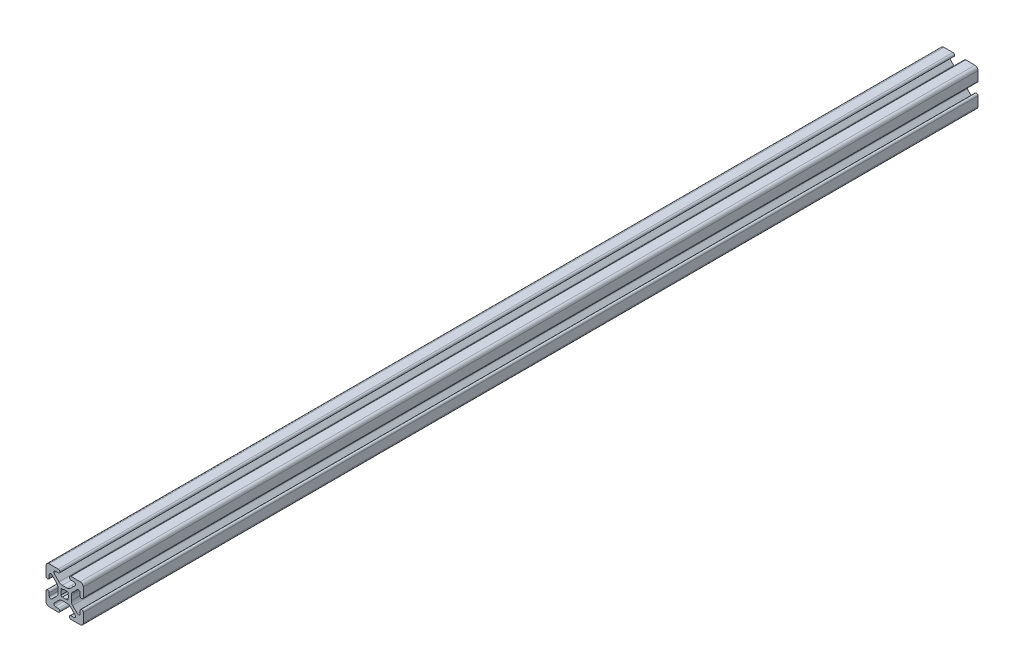
SolidWorks part; units mm, degrees
ref_plane "Front Plane" through (0, 0, 0) normal (0, 0, 1) x (1, 0, 0)
ref_plane "Top Plane" through (0, 0, 0) normal (0, 1, 0) x (1, 0, 0)
ref_plane "Right Plane" through (0, 0, 0) normal (1, 0, 0) x (0, 0, -1)
ref_plane "Plane1" through (0, 0, 304.8) normal (0, 0, 1) x (1, 0, 0)
sketch "Sketch1" plane through (0, 0, 304.8) normal (0, 0, 1) x (1, 0, 0)
  line L0 (-12.7, -4.3561) -> (-12.7, -10.5918)
  line L1 (-10.5918, -12.7) -> (-4.3561, -12.7)
  line L2 (-4.3561, -10.4902) -> (-6.3701, -10.4902)
  line L3 (-7.1192, -8.6817) -> (-3.8846, -5.4471)
  line L4 (-1.6396, -4.5172) -> (1.6396, -4.5172)
  line L5 (3.8846, -5.4471) -> (7.1192, -8.6817)
  line L6 (6.3701, -10.4902) -> (4.3561, -10.4902)
  line L7 (4.3561, -12.7) -> (10.5918, -12.7)
  line L8 (12.7, -10.5918) -> (12.7, -4.3561)
  line L9 (10.4902, -4.3561) -> (10.4902, -6.3701)
  line L10 (8.6817, -7.1192) -> (5.4471, -3.8846)
  line L11 (4.5172, -1.6396) -> (4.5172, 1.6396)
  line L12 (5.4471, 3.8846) -> (8.6817, 7.1192)
  line L13 (10.4902, 6.3701) -> (10.4902, 4.3561)
  line L14 (12.7, 4.3561) -> (12.7, 10.5918)
  line L15 (10.5918, 12.7) -> (4.3561, 12.7)
  line L16 (4.3561, 10.4902) -> (6.3701, 10.4902)
  line L17 (7.1192, 8.6817) -> (3.8846, 5.4471)
  line L18 (1.6396, 4.5172) -> (-1.6396, 4.5172)
  line L19 (-3.8846, 5.4471) -> (-7.1192, 8.6817)
  line L20 (-6.3701, 10.4902) -> (-4.3561, 10.4902)
  line L21 (-4.3561, 12.7) -> (-10.5918, 12.7)
  line L22 (-12.7, 10.5918) -> (-12.7, 4.3561)
  line L23 (-10.4902, 4.3561) -> (-10.4902, 6.3701)
  line L24 (-8.6817, 7.1192) -> (-5.4471, 3.8846)
  line L25 (-4.5172, 1.6396) -> (-4.5172, -1.6396)
  line L26 (-5.4471, -3.8846) -> (-8.6817, -7.1192)
  line L27 (-10.4902, -6.3701) -> (-10.4902, -4.3561)
  arc A0 (-2.2319, 1.3405) -> (-1.3405, 2.2319) centre (-1.841, 1.841) cw
  arc A1 (-1.3405, 2.2319) -> (1.3405, 2.2319) centre (0, 0) cw
  arc A2 (1.3405, 2.2319) -> (2.2319, 1.3405) centre (1.841, 1.841) cw
  arc A3 (2.2319, 1.3405) -> (2.2319, -1.3405) centre (0, 0) cw
  arc A4 (2.2319, -1.3405) -> (1.3405, -2.2319) centre (1.841, -1.841) cw
  arc A5 (1.3405, -2.2319) -> (-1.3405, -2.2319) centre (0, 0) cw
  arc A6 (-1.3405, -2.2319) -> (-2.2319, -1.3405) centre (-1.841, -1.841) cw
  arc A7 (-2.2319, -1.3405) -> (-2.2319, 1.3405) centre (0, 0) cw
  arc A8 (-10.4902, -4.3561) -> (-12.7, -4.3561) centre (-11.5951, -4.3561) ccw
  arc A9 (-12.7, -10.5918) -> (-10.5918, -12.7) centre (-10.5918, -10.5918) ccw
  arc A10 (-4.3561, -12.7) -> (-4.3561, -10.4902) centre (-4.3561, -11.5951) ccw
  arc A11 (-6.3701, -10.4902) -> (-7.1192, -8.6817) centre (-6.3701, -9.4308) cw
  arc A12 (-3.8846, -5.4471) -> (-1.6396, -4.5172) centre (-1.6396, -7.6922) cw
  arc A13 (1.6396, -4.5172) -> (3.8846, -5.4471) centre (1.6396, -7.6922) cw
  arc A14 (7.1192, -8.6817) -> (6.3701, -10.4902) centre (6.3701, -9.4308) cw
  arc A15 (4.3561, -10.4902) -> (4.3561, -12.7) centre (4.3561, -11.5951) ccw
  arc A16 (10.5918, -12.7) -> (12.7, -10.5918) centre (10.5918, -10.5918) ccw
  arc A17 (12.7, -4.3561) -> (10.4902, -4.3561) centre (11.5951, -4.3561) ccw
  arc A18 (10.4902, -6.3701) -> (8.6817, -7.1192) centre (9.4308, -6.3701) cw
  arc A19 (5.4471, -3.8846) -> (4.5172, -1.6396) centre (7.6922, -1.6396) cw
  arc A20 (4.5172, 1.6396) -> (5.4471, 3.8846) centre (7.6922, 1.6396) cw
  arc A21 (8.6817, 7.1192) -> (10.4902, 6.3701) centre (9.4308, 6.3701) cw
  arc A22 (10.4902, 4.3561) -> (12.7, 4.3561) centre (11.5951, 4.3561) ccw
  arc A23 (12.7, 10.5918) -> (10.5918, 12.7) centre (10.5918, 10.5918) ccw
  arc A24 (4.3561, 12.7) -> (4.3561, 10.4902) centre (4.3561, 11.5951) ccw
  arc A25 (6.3701, 10.4902) -> (7.1192, 8.6817) centre (6.3701, 9.4308) cw
  arc A26 (3.8846, 5.4471) -> (1.6396, 4.5172) centre (1.6396, 7.6922) cw
  arc A27 (-1.6396, 4.5172) -> (-3.8846, 5.4471) centre (-1.6396, 7.6922) cw
  arc A28 (-7.1192, 8.6817) -> (-6.3701, 10.4902) centre (-6.3701, 9.4308) cw
  arc A29 (-4.3561, 10.4902) -> (-4.3561, 12.7) centre (-4.3561, 11.5951) ccw
  arc A30 (-10.5918, 12.7) -> (-12.7, 10.5918) centre (-10.5918, 10.5918) ccw
  arc A31 (-12.7, 4.3561) -> (-10.4902, 4.3561) centre (-11.5951, 4.3561) ccw
  arc A32 (-10.4902, 6.3701) -> (-8.6817, 7.1192) centre (-9.4308, 6.3701) cw
  arc A33 (-5.4471, 3.8846) -> (-4.5172, 1.6396) centre (-7.6922, 1.6396) cw
  arc A34 (-4.5172, -1.6396) -> (-5.4471, -3.8846) centre (-7.6922, -1.6396) cw
  arc A35 (-8.6817, -7.1192) -> (-10.4902, -6.3701) centre (-9.4308, -6.3701) cw
extrude "Boss-Extrude1" add sketch "Sketch1" against normal blind 609.6
